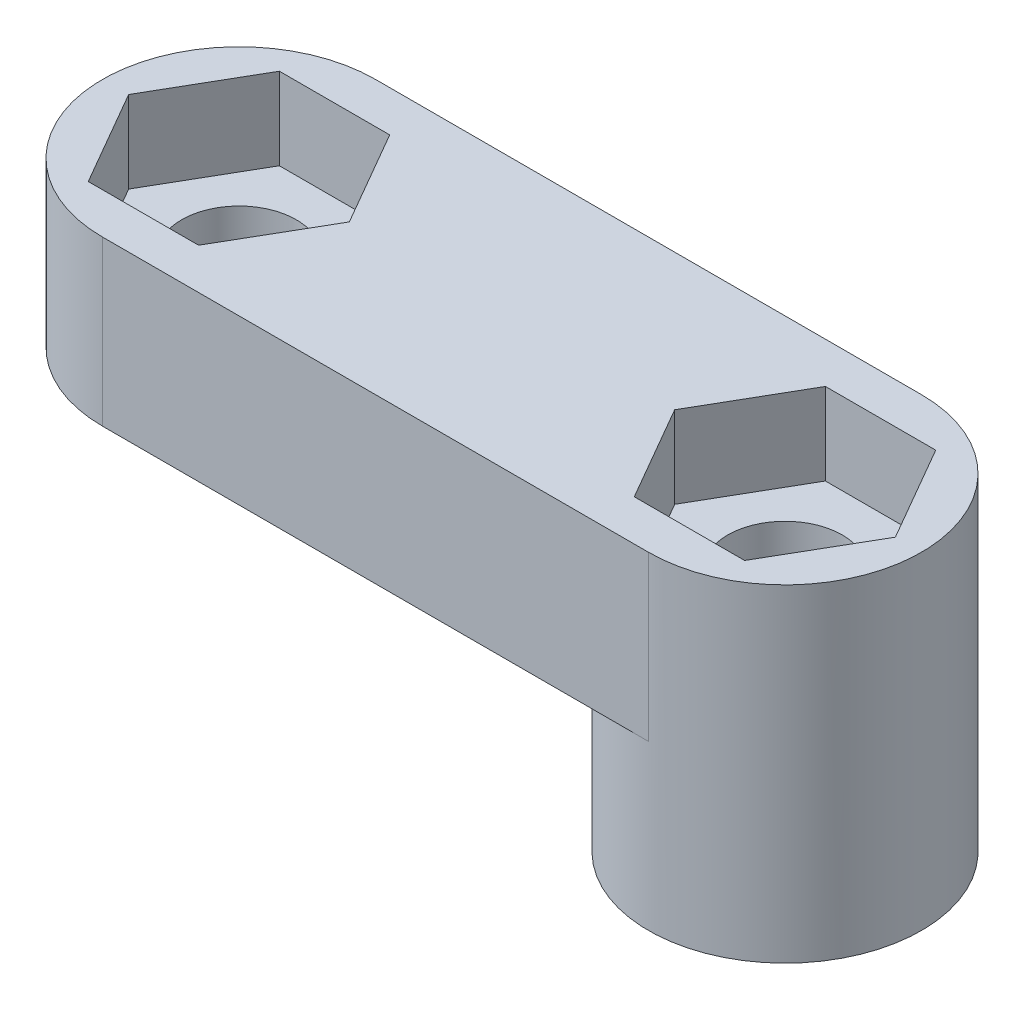
SolidWorks part; units mm, degrees
ref_plane "Front Plane" through (0, 0, 0) normal (0, 0, 1) x (1, 0, 0)
ref_plane "Top Plane" through (0, 0, 0) normal (0, 1, 0) x (1, 0, 0)
ref_plane "Right Plane" through (0, 0, 0) normal (1, 0, 0) x (0, 0, -1)
sketch "Sketch1" plane through (0, 0, 0) normal (0, 1, 0) x (1, 0, 0)
  line L0 (-10, 0) -> (10, 0) construction
  line L1 (-10, 5) -> (10, 5)
  line L2 (-10, -5) -> (10, -5)
  arc A0 (-10, 5) -> (-10, -5) centre (-10, 0) ccw
  arc A1 (10, -5) -> (10, 5) centre (10, 0) ccw
  circle A2 centre (10, 0) radius 2.1
  circle A3 centre (-10, 0) radius 2.1
  point P2 (0, 0)
  dimension "D3" = 4.2
  dimension "D4" = 4.2
  dimension "D1" = 10
  dimension "D2" = 20
extrude "Boss-Extrude1" add sketch "Sketch1" along normal mid plane 6
sketch "Sketch2" plane through (0, 3, 0) normal (0, 1, 0) x (1, 0, 0)
  line L1 (-5.9585, 0) -> (-7.9793, 3.5)
  line L2 (-7.9793, 3.5) -> (-12.0207, 3.5)
  line L3 (-12.0207, 3.5) -> (-14.0415, 0)
  line L4 (-14.0415, 0) -> (-12.0207, -3.5)
  line L5 (-12.0207, -3.5) -> (-7.9793, -3.5)
  line L6 (-7.9793, -3.5) -> (-5.9585, 0)
  line L7 (14.0415, 0) -> (12.0207, 3.5)
  line L8 (12.0207, 3.5) -> (7.9793, 3.5)
  line L9 (7.9793, 3.5) -> (5.9585, 0)
  line L10 (5.9585, 0) -> (7.9793, -3.5)
  line L11 (7.9793, -3.5) -> (12.0207, -3.5)
  line L12 (12.0207, -3.5) -> (14.0415, 0)
  circle A0 centre (-10, 0) radius 3.5 construction
  circle A1 centre (10, 0) radius 3.5 construction
  dimension "D1" = 7
  dimension "D2" = 7
extrude "Cut-Extrude1" cut sketch "Sketch2" against normal blind 3
sketch "Sketch3" plane through (0, -3, 0) normal (0, -1, 0) x (1, 0, 0)
  circle A0 centre (10, 0) radius 2.1
  circle A1 centre (10, 0) radius 5
extrude "Boss-Extrude2" add sketch "Sketch3" along normal blind 6
